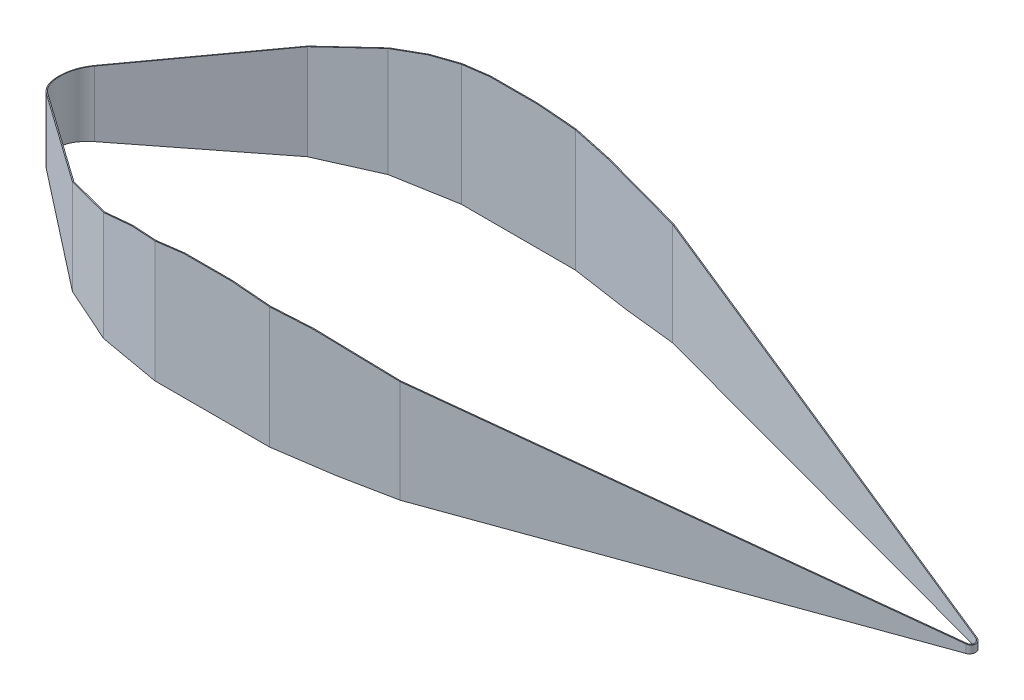
SolidWorks part; units mm, degrees
ref_plane "Front Plane" through (0, 0, 0) normal (0, 0, 1) x (1, 0, 0)
ref_plane "Top Plane" through (0, 0, 0) normal (0, 1, 0) x (1, 0, 0)
ref_plane "Right Plane" through (0, 0, 0) normal (1, 0, 0) x (0, 0, -1)
sketch "Sketch1" plane through (0, 0, 0) normal (0, 1, 0) x (1, 0, 0)
  line L0 (161.4098, 126.0887) -> (784.13, 612.54)
  line L1 (784.13, 612.54) -> (1076.464, 742.696)
  line L2 (1076.464, 742.696) -> (1401.451, 800)
  line L3 (1401.451, 800) -> (1997.019, 800)
  line L4 (1997.019, 800) -> (2590.582, 712.35)
  line L5 (2590.582, 712.35) -> (4854.8761, 28.7196)
  line L6 (4854.8761, -28.7196) -> (2590.582, -712.35)
  line L7 (2590.582, -712.35) -> (1997.019, -800)
  line L8 (1997.019, -800) -> (1401.451, -800)
  line L9 (1401.451, -800) -> (1076.464, -742.696)
  line L10 (1076.464, -742.696) -> (784.13, -612.54)
  line L11 (784.13, -612.54) -> (161.4098, -126.0887)
  arc A0 (161.4098, 126.0887) -> (161.4098, -126.0887) centre (259.9067, 0) ccw
  arc A1 (4854.8761, 28.7196) -> (4854.8761, -28.7196) centre (4846.2052, 0) cw
  point P15 (0, 0)
  point P18 (4950, 0)
  dimension "r0" = 160
  dimension "r6" = 30
  dimension "x1" = 784.13
  dimension "x2" = 1076.464
  dimension "x3" = 1401.451
  dimension "x4" = 1997.019
  dimension "x5" = 2590.582
  dimension "x6" = 4950
  dimension "x7" = 2590.582
  dimension "x8" = 1997.019
  dimension "x9" = 1401.451
  dimension "x10" = 1076.464
  dimension "x11" = 784.13
  dimension "y1" = 612.54
  dimension "y2" = 742.696
  dimension "y3" = 800
  dimension "y5" = 712.35
  dimension "y7" = 712.35
  dimension "y8" = 800
  dimension "y10" = 742.696
  dimension "y11" = 612.54
extrude "TopView_Extrude" add sketch "Sketch1" along normal blind 800
shell "Shell1" thickness 5
sketch "Sketch2" plane through (0, 0, 0) normal (0, 0, 1) x (1, 0, 0)
  line L0 (0, 300) -> (0, 332.8541)
  line L1 (113.6551, 478.3843) -> (1255.921, 763.655)
  line L2 (1255.921, 763.655) -> (1551.451, 800)
  line L3 (1551.451, 800) -> (1800, 800)
  line L4 (1800, 800) -> (2197.056, 765.81)
  line L5 (2197.056, 765.81) -> (4950, 288.165)
  line L6 (4950, 288.165) -> (4950, 265.638)
  line L7 (4950, 265.638) -> (2301.451, 150)
  line L8 (2301.451, 150) -> (150, 150)
  arc A0 (0, 300) -> (150, 150) centre (150, 300) ccw
  arc A1 (0, 332.8541) -> (113.6551, 478.3843) centre (150, 332.8541) cw
  point P12 (0, 150)
  point P15 (0, 450)
  dimension "r0" = 150
  dimension "r1" = 150
  dimension "x2" = 1255.921
  dimension "x3" = 1551.451
  dimension "x4" = 1800
  dimension "x5" = 2197.056
  dimension "x6" = 4950
  dimension "x8" = 2301.451
  dimension "y0" = 150
  dimension "y1" = 450
  dimension "y2" = 763.655
  dimension "y3" = 800
  dimension "y5" = 765.81
  dimension "y6" = 288.165
  dimension "y7" = 265.638
extrude "SideProfile_Cut" cut sketch "Sketch2" against normal through all and the other way through all flip side to cut
